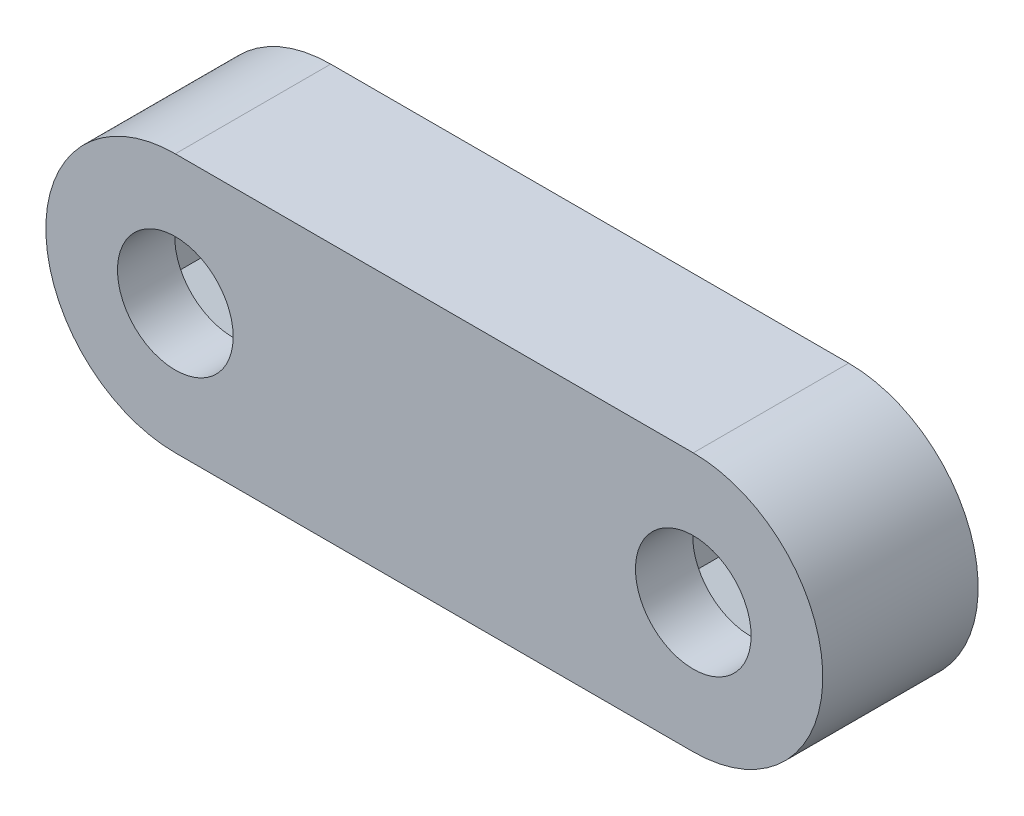
SolidWorks part; units mm, degrees
ref_plane "Front" through (0, 0, 0) normal (0, 0, 1) x (1, 0, 0)
ref_plane "Top" through (0, 0, 0) normal (0, 1, 0) x (1, 0, 0)
ref_plane "Right" through (0, 0, 0) normal (1, 0, 0) x (0, 0, -1)
sketch "Sketch1" plane through (0, 0, 0) normal (0, 0, 1) x (1, 0, 0)
  line L0 (0, 0) -> (15, 0) construction
  line L1 (15, 0) -> (75, 0)
  line L3 (15, 30) -> (75, 30)
  line L5 (0, 0) -> (0, 15) construction
  line L6 (15, 15) -> (15, 23.3716) construction
  line L7 (15, 23.3716) -> (7.75, 19.1858)
  line L8 (7.75, 19.1858) -> (7.75, 10.8142)
  line L9 (7.75, 10.8142) -> (15, 6.6284)
  line L10 (15, 6.6284) -> (22.25, 10.8142)
  line L11 (22.25, 10.8142) -> (22.25, 19.1858)
  line L12 (22.25, 19.1858) -> (15, 23.3716)
  line L13 (75, 23.3716) -> (67.75, 19.1858)
  line L14 (67.75, 19.1858) -> (67.75, 10.8142)
  line L15 (67.75, 10.8142) -> (75, 6.6284)
  line L16 (75, 6.6284) -> (82.25, 10.8142)
  line L17 (82.25, 10.8142) -> (82.25, 19.1858)
  line L18 (82.25, 19.1858) -> (75, 23.3716)
  line L19 (75, 15) -> (75, 23.3716) construction
  arc A0 (15, 30) -> (15, 0) centre (15, 15) ccw
  arc A1 (75, 0) -> (75, 30) centre (75, 15) ccw
  circle A2 centre (15, 15) radius 8.3716 construction
  circle A3 centre (75, 15) radius 8.3716 construction
  point P9 (90, 15)
  dimension "D1" = 30
  dimension "D2" = 90
  dimension "D3" = 14.5
  dimension "D4" = 14.5
extrude "Boss-Extrude1" add sketch "Sketch1" along normal blind 18
sketch "Sketch2" plane through (0, 0, 0) normal (0, 0, -1) x (-1, 0, 0)
  line L0 (-15, 15) -> (-15, 25) construction
  line L1 (-15, 15) -> (-22.25, 15) construction
  line L2 (-22.25, 10.8142) -> (-22.25, 19.1858) construction
  circle A0 centre (-75, 15) radius 10
  circle A2 centre (-15, 15) radius 10
  dimension "D1" = 20
  dimension "D2" = 20
extrude "Cut-Extrude1" cut sketch "Sketch2" against normal blind 5.6
sketch "Sketch3" plane through (0, 0, 18) normal (0, 0, 1) x (1, 0, 0)
  line L0 (22.25, 15) -> (7.75, 15) construction
  line L1 (22.25, 10.8142) -> (22.25, 19.1858) construction
  line L2 (7.75, 19.1858) -> (7.75, 10.8142) construction
  line L3 (67.75, 15) -> (82.25, 15) construction
  line L4 (67.75, 19.1858) -> (67.75, 10.8142) construction
  line L5 (82.25, 10.8142) -> (82.25, 19.1858) construction
  circle A0 centre (15, 15) radius 6.7
  circle A1 centre (75, 15) radius 6.7
  circle A2 centre (75, 15) radius 8.3716
  circle A3 centre (15, 15) radius 8.3716
  dimension "D1" = 13.4
  dimension "D2" = 13.4
extrude "Boss-Extrude2" add sketch "Sketch3" against normal blind 6.63
